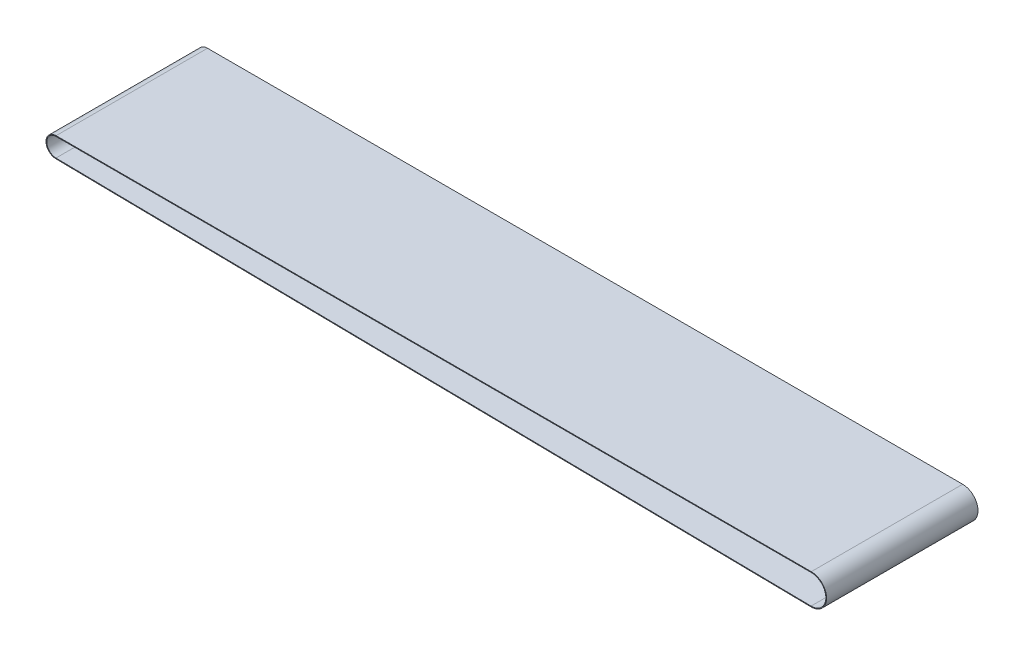
SolidWorks part; units mm, degrees
material "Märtens PU-G/2"
ref_plane "Ebene vorne" through (0, 0, 0) normal (0, 0, 1) x (1, 0, 0)
ref_plane "Ebene oben" through (0, 0, 0) normal (0, 1, 0) x (1, 0, 0)
ref_plane "Ebene rechts" through (0, 0, 0) normal (1, 0, 0) x (0, 0, -1)
sketch "Skizze2" plane through (0, 0, 0) normal (0, 0, 1) x (1, 0, 0)
  line L0 (0, 0) -> (1, 0) construction
  line L1 (0, 0) -> (0, 1) construction
  line L4 (-2020, 217) -> (0, 217)
  line L5 (-0.5406, 139.0037) -> (-2020.3465, 167.0024)
  arc A1 (-2020.3465, 167.0024) -> (-2020, 217) centre (-2020, 192) cw
  arc A2 (0, 217) -> (-0.5406, 139.0037) centre (0, 178) cw
sketch "Skizze3" plane through (0, 0, 0) normal (1, 0, 0) x (0, 0, -1)
  line L1 (202.5, 219) -> (-202.5, 219)
  line L2 (202.5, 219) -> (202.5, 217)
  line L3 (202.5, 217) -> (0, 217)
  line L4 (-202.5, 219) -> (-202.5, 217)
  line L7 (0, 219) -> (0, 217) construction
  line L8 (0, 217) -> (-202.5, 217)
  dimension "D1" = 405
  dimension "D2" = 2
sweep "Austragung1" add profiles "Skizze3" path "Skizze2"
